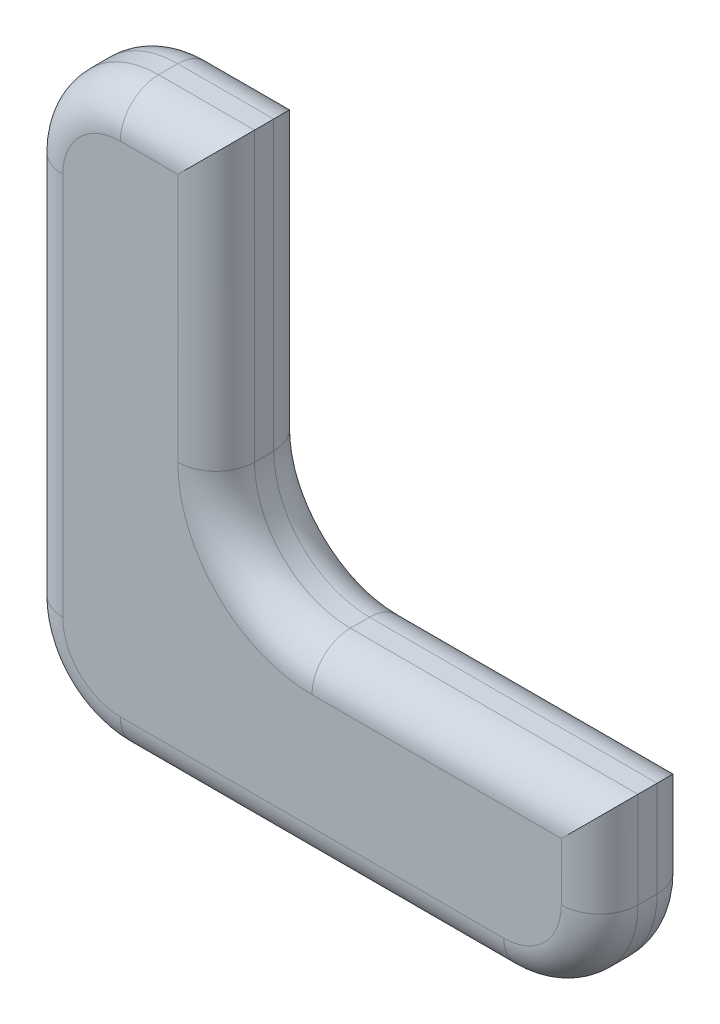
SolidWorks part; units mm, degrees
ref_plane "Front Plane" through (0, 0, 0) normal (0, 0, 1) x (1, 0, 0)
ref_plane "Top Plane" through (0, 0, 0) normal (0, 1, 0) x (1, 0, 0)
ref_plane "Right Plane" through (0, 0, 0) normal (1, 0, 0) x (0, 0, -1)
sketch "Sketch1" plane through (0, 0, 0) normal (0, 0, 1) x (1, 0, 0)
  line L1 (0, 0) -> (10, 0)
  line L2 (0, 0) -> (0, -10)
  line L3 (0, -10) -> (10, -10)
  line L4 (10, 0) -> (10, -10)
  dimension "D1" = 10
  dimension "D2" = 10
extrude "Boss-Extrude1" add sketch "Sketch1" along normal blind 5
sketch "Sketch2" plane through (0, 0, 0) normal (0, 1, 0) x (1, 0, 0)
  line L4 (10, 0) -> (0, 0)
  line L5 (0, 0) -> (0, -5)
  line L6 (0, -5) -> (10, -5)
  line L7 (10, -5) -> (10, 0)
  line L8 (10, 0) -> (0, 0)
  line L9 (0, 0) -> (0, -5)
  line L10 (0, -5) -> (10, -5)
  line L11 (10, -5) -> (10, 0)
  dimension "D1" = 0
extrude "Boss-Extrude2" add sketch "Sketch2" along normal blind 20
sketch "Sketch3" plane through (10, 0, 0) normal (1, 0, 0) x (0, 0, -1)
  line L0 (0, -10) -> (0, 20) construction
  line L1 (-5, -10) -> (0, -10)
  line L2 (-5, -10) -> (-5, 0)
  line L3 (-5, 0) -> (0, 0)
  line L4 (0, -10) -> (0, 0)
  dimension "D1" = 10
extrude "Boss-Extrude3" add sketch "Sketch3" along normal blind 20
fillet "Fillet1" radius 5 4 edges at (30, -10, 2.5) (0, 20, 2.5) (10, 0, 2.5) (0, -10, 2.5)
fillet "Fillet2" radius 2 20 edges at (1.4645, -8.5355, 5) (0, 5, 5) (1.4645, 18.5355, 5) (7.5, 20, 5) (10, 12.5, 5) (11.4645, 1.4645, 5) (22.5, 0, 5) (30, -2.5, 5) (28.5355, -8.5355, 5) (15, -10, 5) (22.5, 0, 0) (11.4645, 1.4645, 0) (10, 12.5, 0) (7.5, 20, 0) (1.4645, 18.5355, 0) (0, 5, 0) (1.4645, -8.5355, 0) (15, -10, 0) (28.5355, -8.5355, 0) (30, -2.5, 0)
